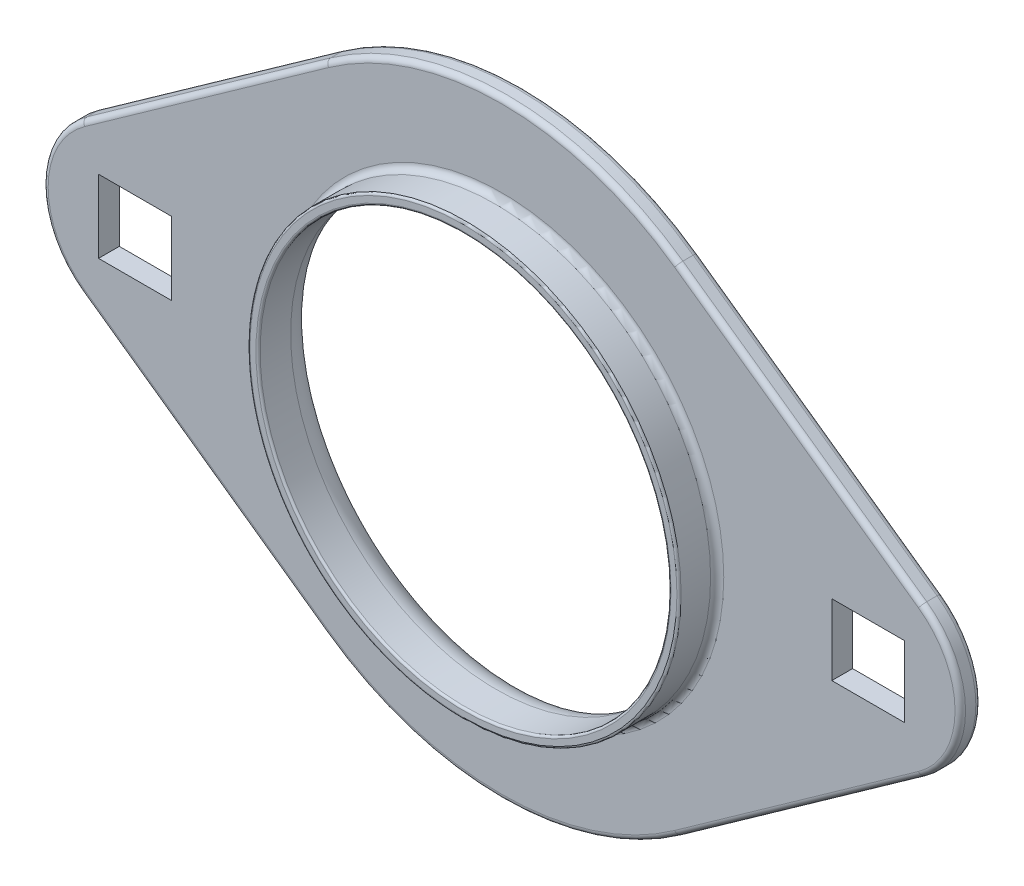
SolidWorks part; units mm, degrees
material "Plain Carbon Steel"
ref_plane "Front Plane" through (0, 0, 0) normal (0, 0, 1) x (1, 0, 0)
ref_plane "Top Plane" through (0, 0, 0) normal (0, 1, 0) x (1, 0, 0)
ref_plane "Right Plane" through (0, 0, 0) normal (1, 0, 0) x (0, 0, -1)
sketch "Sketch1" plane through (0, 0, 0) normal (0, 0, 1) x (1, 0, 0)
  line L0 (0, 103.4806) -> (0, -103.4806) construction
  line L1 (-38.9179, 0) -> (38.9179, 0) construction
  line L2 (16.9993, 23.9567) -> (40.5433, 7.2502)
  line L3 (16.9993, -23.9567) -> (40.5433, -7.2502)
  line L4 (-16.9993, -23.9567) -> (-40.5433, -7.2502)
  line L5 (-16.9993, 23.9567) -> (-40.5433, 7.2502)
  line L6 (-38.9179, 3.5179) -> (-31.8821, 3.5179)
  line L7 (-38.9179, 3.5179) -> (-38.9179, -3.5179)
  line L8 (-38.9179, -3.5179) -> (-31.8821, -3.5179)
  line L9 (-31.8821, 3.5179) -> (-31.8821, -3.5179)
  line L10 (31.8821, 3.4239) -> (38.9179, 3.4239)
  line L11 (31.8821, 3.4239) -> (31.8821, -3.4239)
  line L12 (31.8821, -3.4239) -> (38.9179, -3.4239)
  line L13 (38.9179, 3.4239) -> (38.9179, -3.4239)
  arc A0 (16.9993, 23.9567) -> (-16.9993, 23.9567) centre (0, 0) ccw
  circle A1 centre (0, 0) radius 19.8374
  arc A2 (40.5433, 7.2502) -> (40.5433, -7.2502) centre (35.3987, 0) cw
  arc A3 (16.9993, -23.9567) -> (-16.9993, -23.9567) centre (0, 0) cw
  arc A4 (-40.5433, 7.2502) -> (-40.5433, -7.2502) centre (-35.3987, 0) ccw
  dimension "D1" = 29.3751
  dimension "D2" = 39.6748
  dimension "D3" = 8.89
  dimension "D4" = 70.7974
  dimension "D5" = 7.0358
  dimension "D6" = 38.9179
  dimension "D7" = 6.8478
extrude "Extrude1" add sketch "Sketch1" along normal mid plane 2.0066
sketch "Sketch2" plane through (0, 0, 1.0033) normal (0, 0, 1) x (1, 0, 0)
  circle A0 centre (0, 0) radius 20.8153
  circle A1 centre (0, 0) radius 19.8374 construction
  circle A2 centre (0, 0) radius 19.8374
  dimension "D1" = 41.6306
extrude "Extrude2" add sketch "Sketch2" along normal blind 3.683
fillet "Fillet1" radius 2.54 1 edges at (19.8374, 0, -1.0033)
fillet "Fillet2" radius 0.635 1 edges at (20.8153, 0, 1.0033)
fillet "Fillet3" radius 0.508 16 edges at (28.7713, 15.6034, -1.0033) (44.2887, 0, -1.0033) (28.7713, -15.6034, -1.0033) (0, -29.3751, -1.0033) (-28.7713, -15.6034, -1.0033) (-44.2887, 0, -1.0033) (-28.7713, 15.6034, -1.0033) (28.7713, 15.6034, 1.0033) (44.2887, 0, 1.0033) (28.7713, -15.6034, 1.0033) (0, -29.3751, 1.0033) (-28.7713, -15.6034, 1.0033) (-44.2887, 0, 1.0033) (-28.7713, 15.6034, 1.0033) (0, 29.3751, -1.0033) (0, 29.3751, 1.0033)
fillet "Fillet4" radius 0.2032 2 edges at (20.8153, 0, 4.6863) (19.8374, 0, 4.6863)
